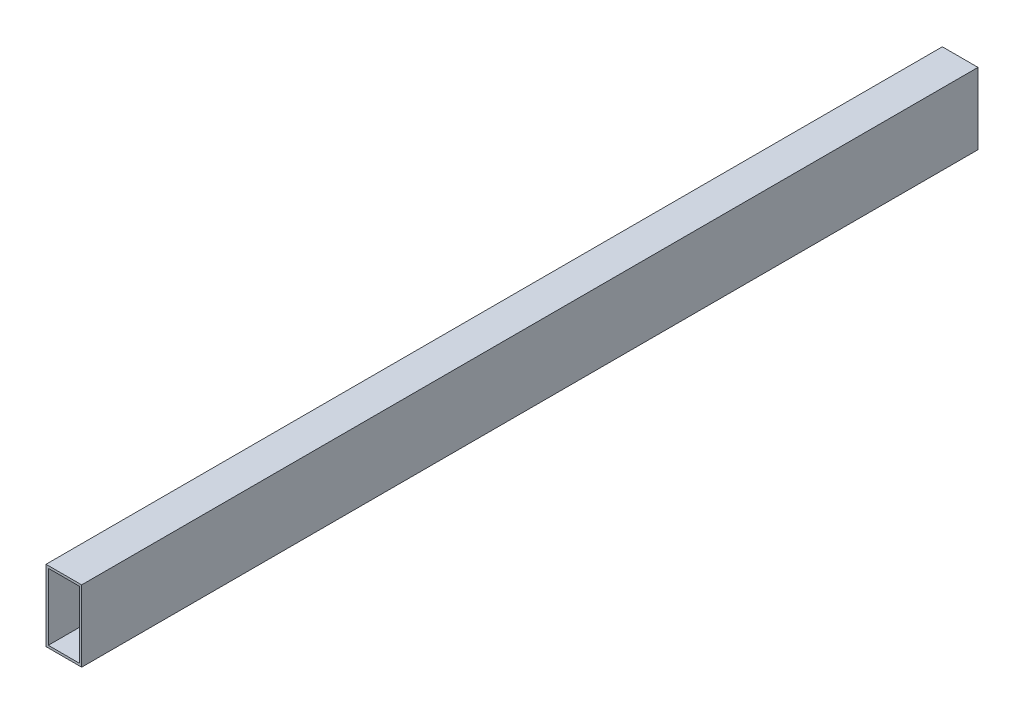
SolidWorks part; units mm, degrees
material "6061 Alloy"
ref_plane "Front Plane" through (0, 0, 0) normal (0, 0, 1) x (1, 0, 0)
ref_plane "Top Plane" through (0, 0, 0) normal (0, 1, 0) x (1, 0, 0)
ref_plane "Right Plane" through (0, 0, 0) normal (1, 0, 0) x (0, 0, -1)
sketch "Sketch1" plane through (0, 0, 0) normal (0, 0, 1) x (1, 0, 0)
  line L1 (-48.4372, -30.1994) -> (-23.0372, -30.1994)
  line L2 (-48.4372, -30.1994) -> (-48.4372, 20.6006)
  line L3 (-48.4372, 20.6006) -> (-23.0372, 20.6006)
  line L4 (-23.0372, -30.1994) -> (-23.0372, 20.6006)
  dimension "D1" = 25.4
  dimension "D2" = 50.8
extrude "Boss-Extrude1" add sketch "Sketch1" along normal blind 638.302
sketch "Sketch2" plane through (0, 0, 638.302) normal (0, 0, 1) x (1, 0, 0)
  line L0 (-48.4372, 20.6006) -> (-48.4372, -30.1994) construction
  line L1 (-46.7862, 18.9496) -> (-24.6882, 18.9496)
  line L2 (-46.7862, 18.9496) -> (-46.7862, -28.5484)
  line L3 (-46.7862, -28.5484) -> (-24.6882, -28.5484)
  line L4 (-24.6882, 18.9496) -> (-24.6882, -28.5484)
  line L5 (-46.7862, 18.9496) -> (-24.6882, -28.5484) construction
  line L6 (-46.7862, -28.5484) -> (-24.6882, 18.9496) construction
  line L7 (-23.0372, -30.1994) -> (-23.0372, 20.6006) construction
  line L8 (-23.0372, 20.6006) -> (-48.4372, 20.6006) construction
  line L9 (-48.4372, -30.1994) -> (-23.0372, -30.1994) construction
  point P0 (-35.7372, -4.7994)
  dimension "D1" = 1.651
  dimension "D2" = 1.651
  dimension "D3" = 1.651
  dimension "D4" = 1.651
extrude "Cut-Extrude1" cut sketch "Sketch2" against normal through all
